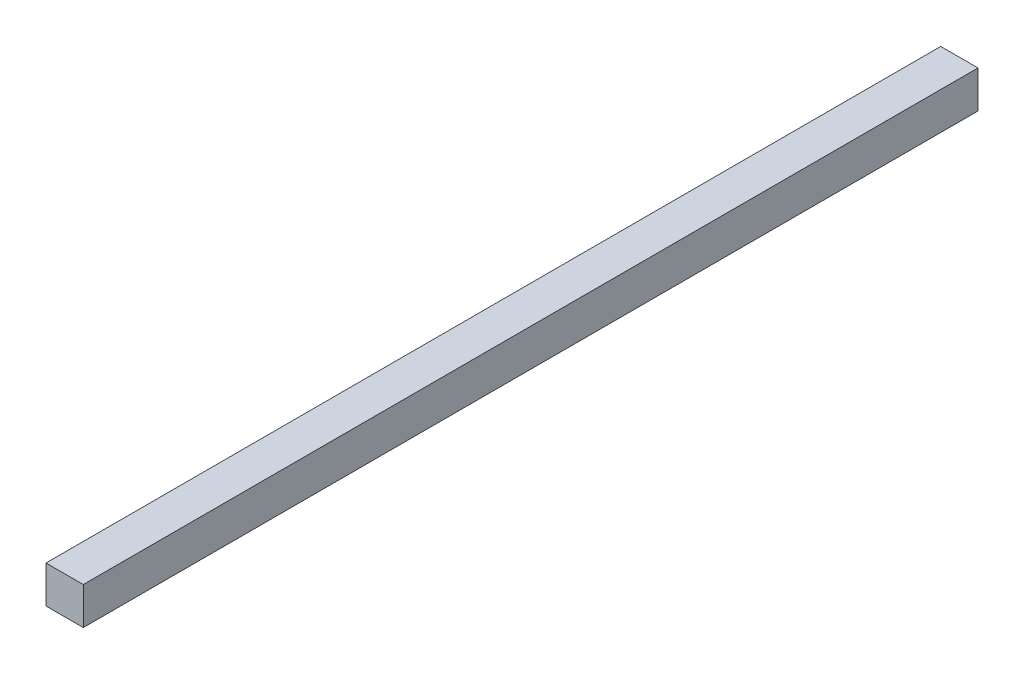
SolidWorks part; units mm, degrees
material "Balsa"
ref_plane "Front Plane" through (0, 0, 0) normal (0, 0, 1) x (1, 0, 0)
ref_plane "Top Plane" through (0, 0, 0) normal (0, 1, 0) x (1, 0, 0)
ref_plane "Right Plane" through (0, 0, 0) normal (1, 0, 0) x (0, 0, -1)
sketch "Sketch1" plane through (0, 0, 0) normal (0, 0, 1) x (1, 0, 0)
  line L1 (-3.175, 3.175) -> (3.175, 3.175)
  line L2 (-3.175, 3.175) -> (-3.175, -3.175)
  line L3 (-3.175, -3.175) -> (3.175, -3.175)
  line L4 (3.175, 3.175) -> (3.175, -3.175)
  line L5 (-3.175, 3.175) -> (3.175, -3.175) construction
  line L6 (-3.175, -3.175) -> (3.175, 3.175) construction
  point P0 (0, 0)
  dimension "D1" = 6.35
extrude "Boss-Extrude1" add sketch "Sketch1" along normal blind 152.4
